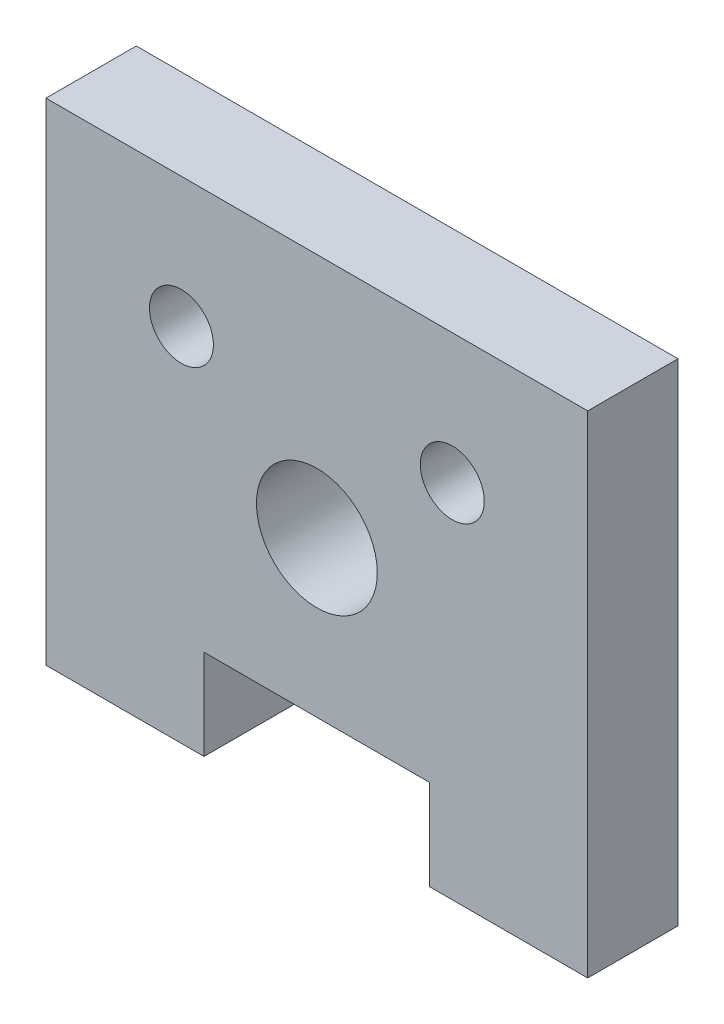
SolidWorks part; units mm, degrees
material "Acrylic (Medium-high impact)"
ref_plane "Front Plane" through (0, 0, 0) normal (0, 0, 1) x (1, 0, 0)
ref_plane "Top Plane" through (0, 0, 0) normal (0, 1, 0) x (1, 0, 0)
ref_plane "Right Plane" through (0, 0, 0) normal (1, 0, 0) x (0, 0, -1)
sketch "Sketch1" plane through (0, 0, 0) normal (0, 0, 1) x (1, 0, 0)
  line L0 (-15.875, -34.544) -> (-15.875, -21.844)
  line L1 (38.1, -34.544) -> (15.875, -34.544)
  line L2 (38.1, -34.544) -> (38.1, 34.544)
  line L3 (38.1, 34.544) -> (-38.1, 34.544)
  line L4 (-38.1, -34.544) -> (-38.1, 34.544)
  line L5 (-15.875, -21.844) -> (15.875, -21.844)
  line L6 (15.875, -21.844) -> (15.875, -34.544)
  line L7 (-15.875, -34.544) -> (-38.1, -34.544)
  circle A0 centre (0, 0) radius 8.5
  circle A1 centre (19.05, 16.256) radius 4.5
  circle A2 centre (-19.05, 16.256) radius 4.5
  point P0 (0, 0)
  point P6 (-38.1, 0)
  point P7 (0, 34.544)
  dimension "D3" = 17
  dimension "D4" = 9
  dimension "D1" = 76.2
  dimension "D2" = 69.088
  dimension "D5" = 19.05
  dimension "D6" = 50.8
  dimension "D7" = 19.05
  dimension "D8" = 31.75
  dimension "D9" = 12.7
extrude "Boss-Extrude1" add sketch "Sketch1" along normal blind 12.7
